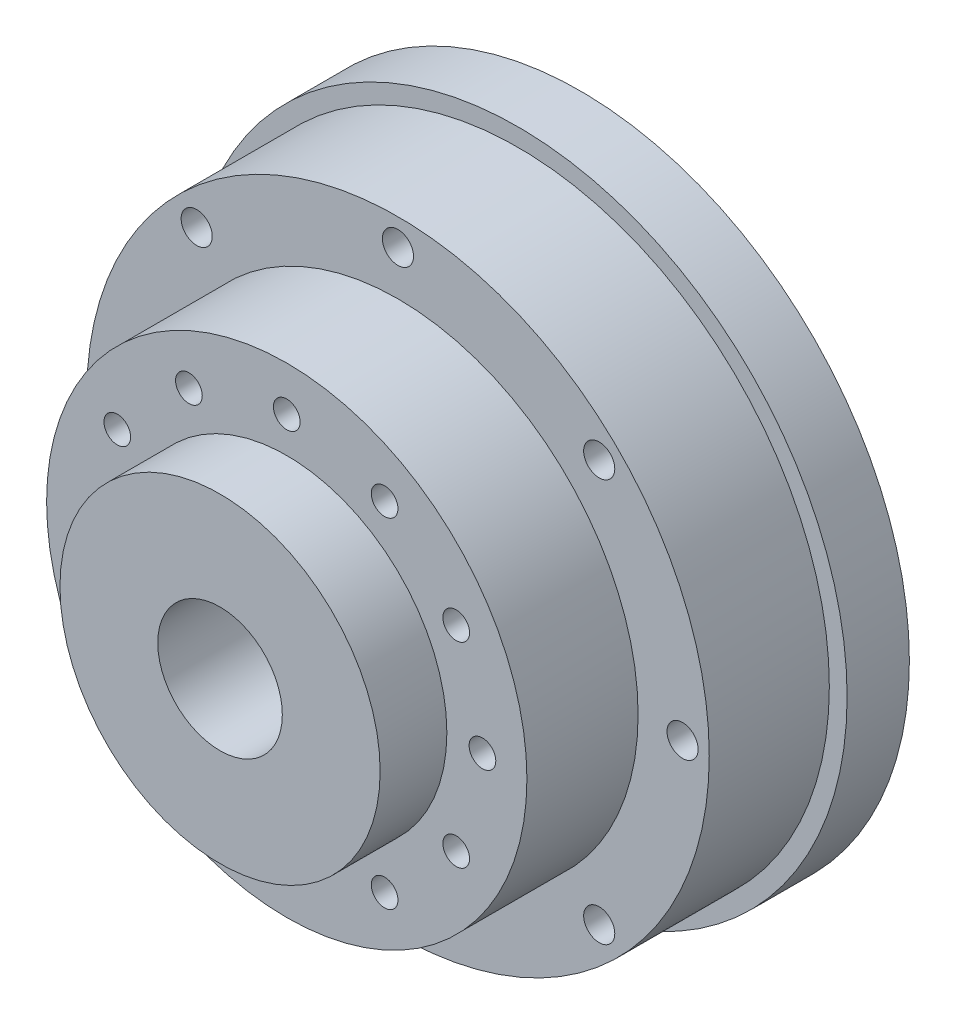
SolidWorks part; units mm, degrees
ref_plane "Спереди" through (0, 0, 0) normal (0, 0, 1) x (1, 0, 0)
ref_plane "Сверху" through (0, 0, 0) normal (0, 1, 0) x (1, 0, 0)
ref_plane "Справа" through (0, 0, 0) normal (1, 0, 0) x (0, 0, -1)
other "Configuration Table"
sketch "Эскиз1" plane through (0, 0, 0) normal (0, 0, 1) x (1, 0, 0)
  circle A0 centre (0, 0) radius 37
  dimension "D1" = 74
extrude "Бобышка-Вытянуть1" add sketch "Эскиз1" along normal blind 7
sketch "Эскиз2" plane through (0, 0, 7) normal (0, 0, 1) x (1, 0, 0)
  circle A0 centre (0, 0) radius 35
  dimension "D1" = 70
extrude "Бобышка-Вытянуть2" add sketch "Эскиз2" along normal blind 13.5
sketch "Эскиз3" plane through (0, 0, 20.5) normal (0, 0, 1) x (1, 0, 0)
  circle A0 centre (0, 0) radius 27
  dimension "D1" = 54
extrude "Бобышка-Вытянуть3" add sketch "Эскиз3" along normal blind 12.5
sketch "Эскиз4" plane through (0, 0, 33) normal (0, 0, 1) x (1, 0, 0)
  circle A0 centre (0, 0) radius 18
  dimension "D1" = 36
extrude "Бобышка-Вытянуть4" add sketch "Эскиз4" along normal blind 7.5
sketch "Эскиз5" plane through (0, 0, 0) normal (0, 0, -1) x (-1, 0, 0)
  circle A0 centre (0, 0) radius 18
  dimension "D1" = 36
extrude "Бобышка-Вытянуть5" add sketch "Эскиз5" along normal blind 5.5
sketch "Эскиз6" plane through (0, 0, -5.5) normal (0, 0, -1) x (-1, 0, 0)
  circle A0 centre (0, 0) radius 10
  dimension "D1" = 20
extrude "Бобышка-Вытянуть6" add sketch "Эскиз6" along normal blind 6.5
sketch "Эскиз7" plane through (0, 0, -12) normal (0, 0, -1) x (-1, 0, 0)
  circle A0 centre (0, 0) radius 7
  dimension "D1" = 14
extrude "Вырез-Вытянуть1" cut sketch "Эскиз7" against normal up to surface (52.5 mm away) up to face at (18, 0, 40.5)
sketch "Эскиз8" plane through (0, 0, 20.5) normal (0, 0, 1) x (1, 0, 0)
  circle A0 centre (0, 32) radius 1.75
  circle A1 centre (22.6274, 22.6274) radius 1.75
  circle A2 centre (32, 0) radius 1.75
  circle A3 centre (22.6274, -22.6274) radius 1.75
  circle A4 centre (0, -32) radius 1.75
  circle A5 centre (-22.6274, -22.6274) radius 1.75
  circle A6 centre (-32, 0) radius 1.75
  circle A7 centre (-22.6274, 22.6274) radius 1.75
  point P19 (0, 0)
  dimension "D2" = 3.5
  dimension "D1" = 32
  dimension "D3" = 8
extrude "Вырез-Вытянуть2" cut sketch "Эскиз8" against normal up to surface (20.5 mm away) up to face at (-18, 0, 0)
sketch "Эскиз9" plane through (0, 0, 33) normal (0, 0, 1) x (1, 0, 0)
  circle A0 centre (0, 22) radius 1.5
  circle A1 centre (11, 19.0526) radius 1.5
  circle A2 centre (19.0526, 11) radius 1.5
  circle A3 centre (22, 0) radius 1.5
  circle A4 centre (19.0526, -11) radius 1.5
  circle A5 centre (11, -19.0526) radius 1.5
  circle A6 centre (0, -22) radius 1.5
  circle A7 centre (-11, -19.0526) radius 1.5
  circle A8 centre (-19.0526, -11) radius 1.5
  circle A9 centre (-22, 0) radius 1.5
  circle A10 centre (-19.0526, 11) radius 1.5
  circle A11 centre (-11, 19.0526) radius 1.5
  point P27 (0, 0)
  dimension "D1" = 3
  dimension "D2" = 22
  dimension "D3" = 12
extrude "Вырез-Вытянуть3" cut sketch "Эскиз9" against normal blind 10
